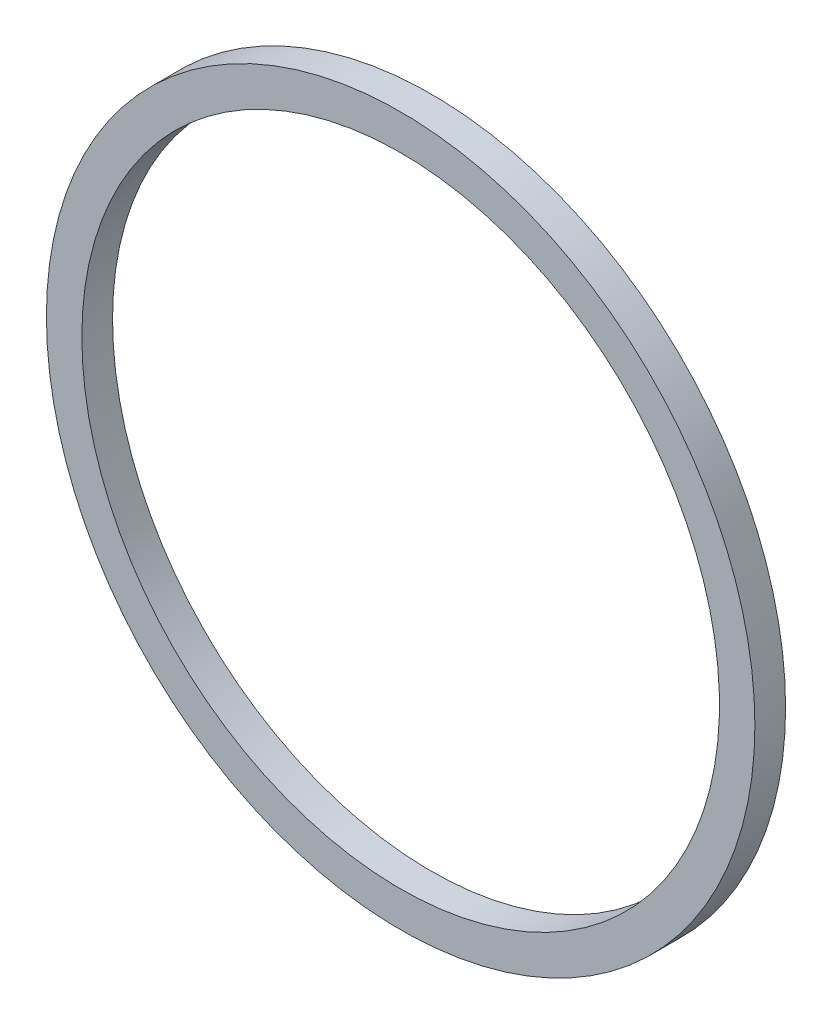
SolidWorks part; units mm, degrees
ref_plane "前视基准面" through (0, 0, 0) normal (0, 0, 1) x (1, 0, 0)
ref_plane "上视基准面" through (0, 0, 0) normal (0, 1, 0) x (1, 0, 0)
ref_plane "右视基准面" through (0, 0, 0) normal (1, 0, 0) x (0, 0, -1)
other "Configuration Table"
sketch "草图1" plane through (0, 0, 0) normal (0, 0, 1) x (1, 0, 0)
  circle A0 centre (0, 0) radius 135
  circle A1 centre (0, 0) radius 150
  dimension "D1" = 270
  dimension "D2" = 15
extrude "凸台-拉伸1" add sketch "草图1" along normal blind 13
